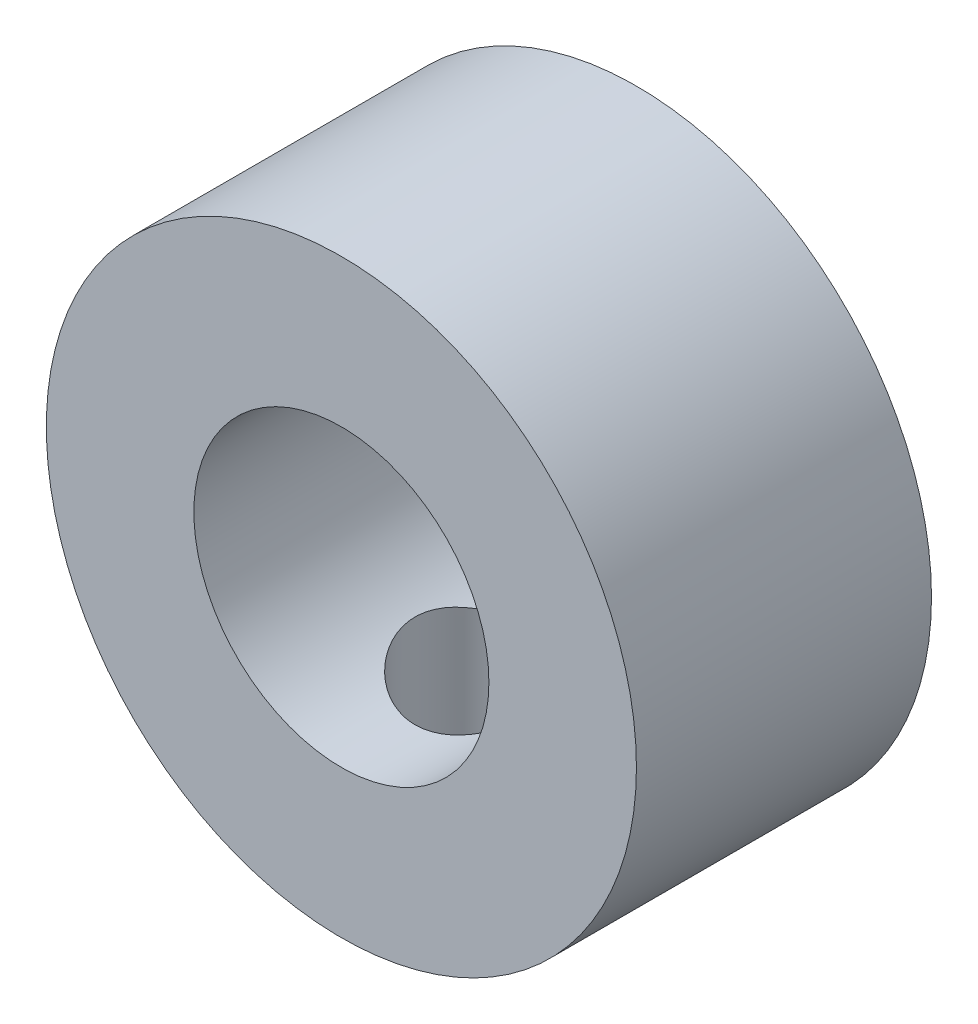
SolidWorks part; units mm, degrees
ref_plane "Plan de face" through (0, 0, 0) normal (0, 0, 1) x (1, 0, 0)
ref_plane "Plan de dessus" through (0, 0, 0) normal (0, 1, 0) x (1, 0, 0)
ref_plane "Plan de droite" through (0, 0, 0) normal (1, 0, 0) x (0, 0, -1)
sketch "Esquisse1" plane through (0, 0, 0) normal (0, 0, 1) x (1, 0, 0)
  circle A0 centre (0, 0) radius 4
  circle A1 centre (0, 0) radius 8
  dimension "D1" = 8
  dimension "D2" = 16
extrude "Boss.-Extru.1" add sketch "Esquisse1" along normal blind 8
sketch "Esquisse2" plane through (0, 0, 0) normal (0, 1, 0) x (1, 0, 0)
  line L0 (0, 0) -> (0, -8) construction
  line L1 (-8, -8) -> (8, -8) construction
  circle A0 centre (0, -4) radius 2
  dimension "D1" = 4
extrude "Enlèv. mat.-Extru.1" cut sketch "Esquisse2" against normal through all
